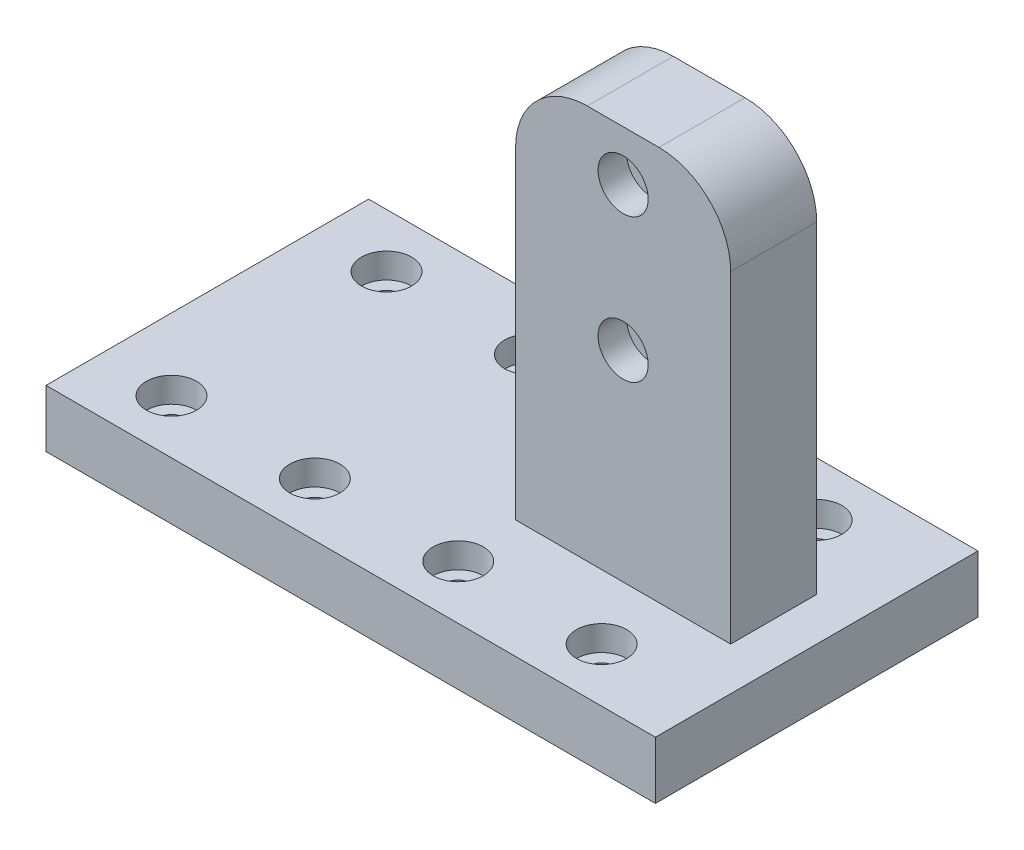
SolidWorks part; units mm, degrees
ref_plane "Front Plane" through (0, 0, 0) normal (0, 0, 1) x (1, 0, 0)
ref_plane "Top Plane" through (0, 0, 0) normal (0, 1, 0) x (1, 0, 0)
ref_plane "Right Plane" through (0, 0, 0) normal (1, 0, 0) x (0, 0, -1)
sketch "Sketch1" plane through (0, 0, 0) normal (0, 1, 0) x (1, 0, 0)
  line L1 (-50, 22.5) -> (50, 22.5)
  line L2 (-50, 22.5) -> (-50, -22.5)
  line L3 (-50, -22.5) -> (50, -22.5)
  line L4 (50, 22.5) -> (50, -22.5)
  dimension "D1" = 100
  dimension "D2" = 22.5
  dimension "D3" = 45
  dimension "D4" = 50
extrude "Boss-Extrude1" add sketch "Sketch1" along normal blind 8
sketch "Sketch2" plane through (0, 8, 0) normal (0, 1, 0) x (1, 0, 0)
  line L0 (50, -22.5) -> (50, 22.5) construction
  circle A0 centre (20, 15) radius 1.75
  circle A1 centre (20, -15) radius 1.75
  circle A2 centre (0, 15) radius 1.75
  circle A3 centre (0, -15) radius 1.75
  circle A4 centre (-20, 15) radius 1.75
  circle A5 centre (-20, -15) radius 1.75
  circle A6 centre (-40, 15) radius 1.75
  circle A7 centre (-40, -15) radius 1.75
  dimension "D1" = 3.5
  dimension "D2" = 3.5
  dimension "D3" = 3.5
  dimension "D4" = 3.5
  dimension "D5" = 3.5
  dimension "D6" = 3.5
  dimension "D7" = 3.5
  dimension "D8" = 3.5
  dimension "D9" = 20
  dimension "D10" = 20
  dimension "D11" = 20
  dimension "D12" = 20
  dimension "D13" = 20
  dimension "D14" = 20
  dimension "D15" = 30
  dimension "D16" = 30
  dimension "D17" = 15
  dimension "D18" = 15
  dimension "D19" = 15
  dimension "D20" = 15
  dimension "D21" = 15
  dimension "D22" = 15
  dimension "D23" = 15
  dimension "D24" = 15
extrude "Cut-Extrude1" cut sketch "Sketch2" against normal blind 8
sketch "Sketch3" plane through (0, 8, 0) normal (0, 1, 0) x (1, 0, 0)
  circle A0 centre (-40, 15) radius 3.5
  circle A1 centre (-20, 15) radius 3.5
  circle A2 centre (0, 15) radius 3.5
  circle A3 centre (20, 15) radius 3.5
  circle A4 centre (-40, -15) radius 3.5
  circle A5 centre (-20, -15) radius 3.5
  circle A6 centre (0, -15) radius 3.5
  circle A7 centre (20, -15) radius 3.5
  dimension "D1" = 7
  dimension "D2" = 7
  dimension "D3" = 7
  dimension "D4" = 7
  dimension "D5" = 7
  dimension "D6" = 7
  dimension "D7" = 7
  dimension "D8" = 7
extrude "Cut-Extrude2" cut sketch "Sketch3" against normal blind 3.5
sketch "Sketch4" plane through (0, 8, 0) normal (0, 1, 0) x (1, 0, 0)
  line L0 (50, -22.5) -> (50, 22.5) construction
  line L1 (-1, 6) -> (29, 6)
  line L2 (-1, 6) -> (-1, -6)
  line L3 (-1, -6) -> (29, -6)
  line L4 (29, 6) -> (29, -6)
  dimension "D1" = 30
  dimension "D2" = 6
  dimension "D3" = 12
  dimension "D4" = 21
extrude "Boss-Extrude2" add sketch "Sketch4" along normal blind 55
sketch "Sketch7" plane through (0, 8, 0) normal (0, 1, 0) x (1, 0, 0)
  line L0 (50, 22.5) -> (-50, 22.5) construction
  line L1 (50, -22.5) -> (35, -22.5)
  line L2 (50, -22.5) -> (50, 22.5)
  line L3 (50, 22.5) -> (35, 22.5)
  line L4 (35, -22.5) -> (35, 22.5)
  dimension "D1" = 15
extrude "Cut-Extrude4" cut sketch "Sketch7" against normal blind 8
sketch "Sketch9" plane through (0, 0, -6) normal (0, 0, -1) x (-1, 0, 0)
  line L0 (-29, 63) -> (1, 63) construction
  line L1 (1, 63) -> (1, 8) construction
  circle A0 centre (-14, 56) radius 1.75
  circle A1 centre (-14, 36) radius 1.75
  dimension "D1" = 7
  dimension "D2" = 20
  dimension "D3" = 15
  dimension "D4" = 3.5
  dimension "D5" = 15
  dimension "D6" = 3.5
extrude "Cut-Extrude6" cut sketch "Sketch9" against normal blind 12
fillet "Fillet1" radius 10 1 edges at (29, 63, 0)
fillet "Fillet2" radius 10 1 edges at (-1, 63, 0)
sketch "Sketch10" plane through (0, 0, 6) normal (0, 0, 1) x (1, 0, 0)
  circle A0 centre (14, 36) radius 3.5
  circle A1 centre (14, 56) radius 3.5
  dimension "D1" = 7
  dimension "D2" = 7
extrude "Cut-Extrude7" cut sketch "Sketch10" against normal blind 4
